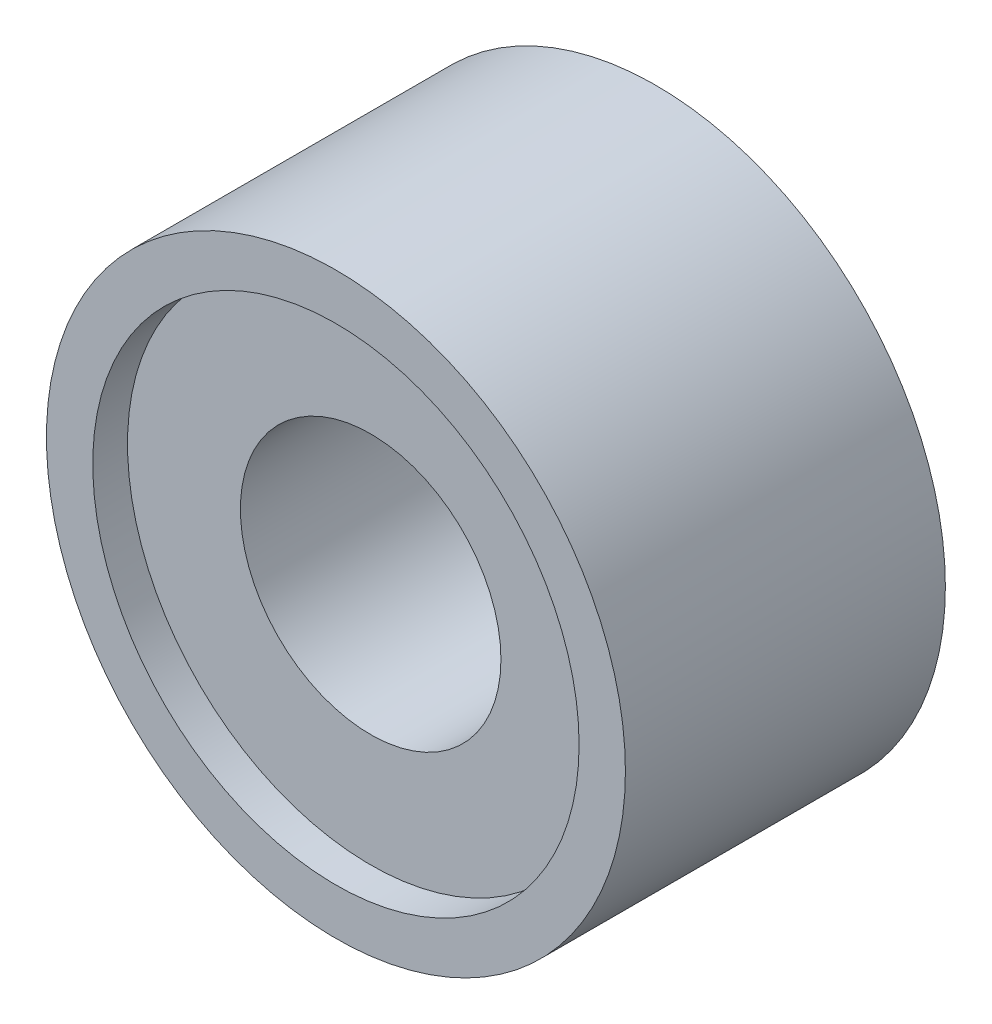
SolidWorks part; units mm, degrees
material "PA Tipo 6"
ref_plane "Alzado" through (0, 0, 0) normal (0, 0, 1) x (1, 0, 0)
ref_plane "Planta" through (0, 0, 0) normal (0, 1, 0) x (1, 0, 0)
ref_plane "Vista lateral" through (0, 0, 0) normal (1, 0, 0) x (0, 0, -1)
sketch "Croquis3" plane through (0, 0, 0) normal (1, 0, 0) x (0, 0, -1)
  line L0 (-45.885, 0) -> (55.0113, 0) construction
  line L1 (0, 0) -> (27.6324, 0)
  line L2 (27.6324, 0) -> (27.6324, -25)
  line L3 (0, 0) -> (0, -25)
  line L8 (27.6324, -25) -> (0, -25)
  dimension "D2" = 50
  dimension "D4" = 27.6324
revolve "Revolución5" add sketch "Croquis3" angle 360 about L0
sketch "Croquis5" plane through (0, 0, 0) normal (0, 0, 1) x (1, 0, 0)
  circle A1 centre (0, 0) radius 11.25
  dimension "D1" = 22.5
extrude "Cortar-Extruir1" cut sketch "Croquis5" against normal through all contours A1
sketch "Croquis6" plane through (0, 0, 0) normal (0, 0, 1) x (1, 0, 0)
  circle A0 centre (0, 0) radius 21
  dimension "D1" = 42
extrude "Cortar-Extruir2" cut sketch "Croquis6" against normal blind 3
